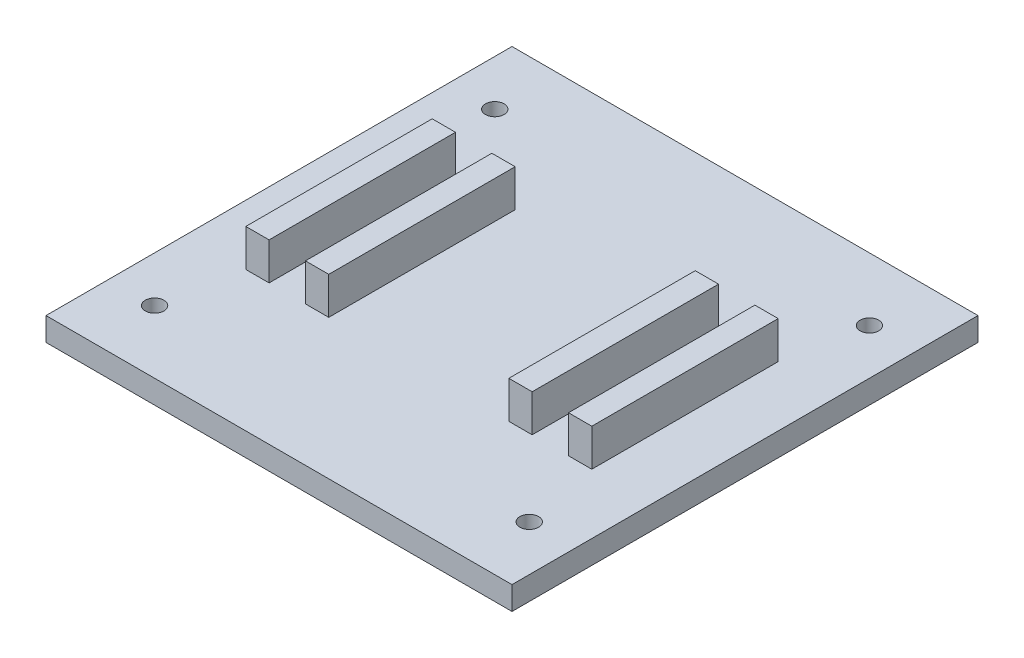
SolidWorks part; units mm, degrees
ref_plane "Front Plane" through (0, 0, 0) normal (0, 0, 1) x (1, 0, 0)
ref_plane "Top Plane" through (0, 0, 0) normal (0, 1, 0) x (1, 0, 0)
ref_plane "Right Plane" through (0, 0, 0) normal (1, 0, 0) x (0, 0, -1)
sketch "Sketch1" plane through (0, 0, 0) normal (0, 1, 0) x (1, 0, 0)
  line L1 (-50, -50) -> (50, -50)
  line L2 (-50, -50) -> (-50, 50)
  line L3 (-50, 50) -> (50, 50)
  line L4 (50, -50) -> (50, 50)
  line L5 (-50, -50) -> (50, 50) construction
  line L6 (-50, 50) -> (50, -50) construction
  point P0 (0, 0)
extrude "Boss-Extrude1" add sketch "Sketch1" along normal blind 5 contours L2 L3 L4 L1
sketch "Sketch2" plane through (0, 5, 0) normal (0, 1, 0) x (1, 0, 0)
  line L0 (19.325, 20) -> (19.325, -20)
  line L2 (-50, -50) -> (50, -50) construction
  line L3 (24.325, 20) -> (19.325, 20)
  line L4 (-32.125, 20) -> (-32.125, -20)
  line L6 (0, 50) -> (0, -50)
  line L7 (-50, 50) -> (50, 50) construction
  line L9 (-32.125, 20) -> (-37.125, 20)
  line L10 (-37.125, 20) -> (-37.125, -20)
  line L11 (-37.125, -20) -> (-32.125, -20)
  line L13 (24.325, -20) -> (19.325, -20)
  line L14 (-24.325, 20) -> (-24.325, -20)
  line L15 (-24.325, -20) -> (-19.325, -20)
  line L16 (-24.325, 20) -> (-19.325, 20)
  line L17 (-19.325, 20) -> (-19.325, -20)
  line L18 (24.325, 20) -> (24.325, -20)
  line L19 (37.125, -20) -> (32.125, -20)
  line L20 (37.125, 20) -> (37.125, -20)
  line L21 (32.125, 20) -> (37.125, 20)
  line L22 (32.125, 20) -> (32.125, -20)
  circle A1 centre (-36.5, -40.4) radius 2
  circle A2 centre (-36.5, 40.4) radius 2
  circle A3 centre (36.5, -40.4) radius 2
  circle A4 centre (36.5, 40.4) radius 2
extrude "Boss-Extrude2" add sketch "Sketch2" along normal blind 8 contours L14 L15 L17 L16 | L10 L11 L4 L9 | L0 L13 L18 L3 | L22 L19 L20 L21
sketch "Sketch4" plane through (0, 5, 0) normal (0, 1, 0) x (1, 0, 0)
  circle A0 centre (40.2, 36.5) radius 2
  circle A1 centre (40.2, -36.5) radius 2
  circle A2 centre (-40.2, -36.5) radius 2
  circle A3 centre (-40.2, 36.5) radius 2
extrude "Cut-Extrude1" cut sketch "Sketch4" against normal blind 8
